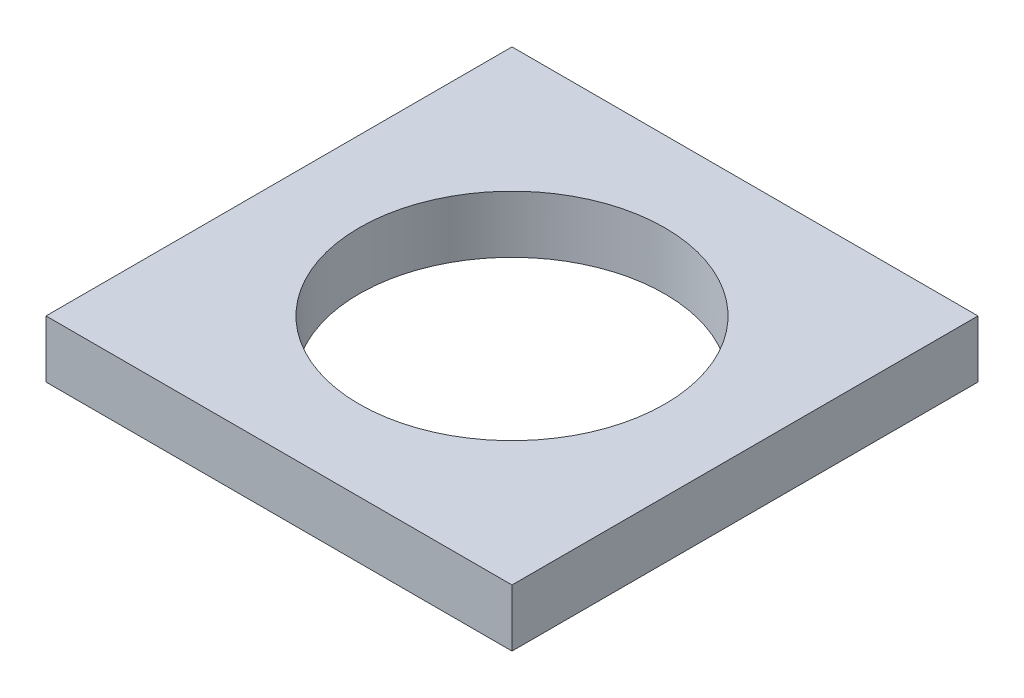
SolidWorks part; units mm, degrees
ref_plane "Front Plane" through (0, 0, 0) normal (0, 0, 1) x (1, 0, 0)
ref_plane "Top Plane" through (0, 0, 0) normal (0, 1, 0) x (1, 0, 0)
ref_plane "Right Plane" through (0, 0, 0) normal (1, 0, 0) x (0, 0, -1)
other "Configuration Table"
sketch "Sketch1" plane through (0, 0, 0) normal (0, 1, 0) x (1, 0, 0)
  line L0 (-6.1, -6.1) -> (6.1, -6.1)
  line L1 (6.1, -6.1) -> (6.1, 6.1)
  line L2 (6.1, 6.1) -> (-6.1, 6.1)
  line L3 (-6.1, 6.1) -> (-6.1, -6.1)
extrude "Seal" add sketch "Sketch1" along normal blind 1.5
sketch "Sketch2" plane through (0, 0, 0) normal (0, 1, 0) x (1, 0, 0)
  circle A0 centre (0, 0) radius 4
  dimension "D1" = 8
extrude "Water_Hole" cut sketch "Sketch2" along normal through all and the other way through all
equation "\"Jar_OD\"= 90  'ASSUMED - Part G fallback - jar outer diameter"
equation "\"Jar_H\"= 120  'ASSUMED - Part G fallback - jar height"
equation "\"Pump_L\"= 45  'ASSUMED - Part G fallback"
equation "\"Pump_W\"= 24  'ASSUMED - Part G fallback"
equation "\"Pump_H\"= 33  'ASSUMED - Part G fallback"
equation "\"Pump_Outlet_OD\"= 7.5  'ASSUMED - Part G fallback"
equation "\"Tube_OD\"= 8  'ASSUMED - Part G fallback"
equation "\"Tube_ID\"= 6  'ASSUMED - Part G fallback"
equation "\"TDS_Body_Dia\"= 12  'ASSUMED - Part G fallback"
equation "\"TDS_Wet_Len\"= 45  'ASSUMED - Part G fallback - length in water"
equation "\"DS_Tube_Dia\"= 6  'ASSUMED - Part G fallback"
equation "\"DS_Tube_Len\"= 50  'ASSUMED - Part G fallback"
equation "\"ORP_Body_Dia\"= 12  'ASSUMED - Part G fallback"
equation "\"ORP_Body_Len\"= 150  'ASSUMED - Part G fallback"
equation "\"ORP_Cap_Dia\"= 16  'ASSUMED - Part G fallback"
equation "\"Turb_W\"= 33  'ASSUMED - Part G fallback - head width"
equation "\"Turb_D\"= 28  'ASSUMED - Part G fallback - head depth"
equation "\"Turb_H\"= 30  'ASSUMED - Part G fallback - head height"
equation "\"Turb_Slot_W\"= 10  'ASSUMED - Part G fallback - slot width"
equation "\"Flow_L\"= 62  'ASSUMED - Part G fallback YF-S201"
equation "\"Flow_W\"= 36  'ASSUMED - Part G fallback"
equation "\"Flow_H\"= 35  'ASSUMED - Part G fallback"
equation "\"Thread_G12_OD\"= 20.955  'ASSUMED - Part G fallback thread G1/2 (major diameter)"
equation "\"Valve_L\"= 75  'ASSUMED - Part G fallback"
equation "\"Valve_W\"= 45  'ASSUMED - Part G fallback"
equation "\"Valve_H\"= 60  'ASSUMED - Part G fallback"
equation "\"Tee_L\"= 40  'ASSUMED - Part G fallback - overall length"
equation "\"Tee_Branch_L\"= 25  'ASSUMED - Part G fallback"
equation "\"Tee_OD\"= 12  'ASSUMED - Part G fallback"
equation "\"LED_Board_L\"= 20  'ASSUMED - Part G fallback"
equation "\"LED_Board_W\"= 20  'ASSUMED - Part G fallback - LED at centre"
equation "\"GUVA_L\"= 20  'ASSUMED - Part G fallback"
equation "\"GUVA_W\"= 12  'ASSUMED - Part G fallback - sensor at centre"
equation "\"Reed_L\"= 27  'ASSUMED - Part G fallback MC-38 half"
equation "\"Reed_W\"= 14  'ASSUMED - Part G fallback"
equation "\"Reed_H\"= 8  'ASSUMED - Part G fallback"
equation "\"ESP_L\"= 51  'ASSUMED - Part G fallback"
equation "\"ESP_W\"= 28  'ASSUMED - Part G fallback"
equation "\"TFT_L\"= 58  'ASSUMED - Part G fallback - board"
equation "\"TFT_W\"= 35  'ASSUMED - Part G fallback - board"
equation "\"TFT_Win_L\"= 35  'ASSUMED - Part G fallback - visible window"
equation "\"TFT_Win_W\"= 28  'ASSUMED - Part G fallback - visible window"
equation "\"Relay_L\"= 50  'ASSUMED - Part G fallback"
equation "\"Relay_W\"= 26  'ASSUMED - Part G fallback"
equation "\"Relay_H\"= 19  'ASSUMED - Part G fallback"
equation "\"Mosfet_L\"= 34  'ASSUMED - Part G fallback"
equation "\"Mosfet_W\"= 17  'ASSUMED - Part G fallback"
equation "\"Mosfet_H\"= 12  'ASSUMED - Part G fallback"
equation "\"TDS_Board_L\"= 42  'ASSUMED - Part G fallback"
equation "\"TDS_Board_W\"= 32  'ASSUMED - Part G fallback"
equation "\"Turb_Board_L\"= 38  'ASSUMED - Part G fallback"
equation "\"Turb_Board_W\"= 28  'ASSUMED - Part G fallback"
equation "\"BNC_Thread_Dia\"= 9.5  'ASSUMED - Part G fallback"
equation "\"Plate_L\"= 420  'ASSUMED - Part G fallback"
equation "\"Plate_W\"= 297  'ASSUMED - Part G fallback"
equation "\"Plate_T\"= 6  'ASSUMED - Part G fallback"
equation "\"Booster_L\"= 150  'ASSUMED - Part G fallback - booster pump"
equation "\"Booster_W\"= 95  'ASSUMED - Part G fallback"
equation "\"Booster_H\"= 100  'ASSUMED - Part G fallback"
equation "\"PTube_OD\"= 6.35  'ASSUMED - Part G fallback - product tube 1/4 inch"
equation "\"Qz_Out\"= 12  'ASSUMED - Part G fallback - quartz channel outside square"
equation "\"Qz_Path\"= 10  'ASSUMED - Part G fallback - quartz channel inside light path"
equation "\"Qz_L\"= 40  'ASSUMED - Part G fallback - quartz channel length"
equation "\"LED860_Dia\"= 5  'ASSUMED - Part G fallback - 860 nm LED"
equation "\"BPW_L\"= 5.4  'ASSUMED - Part G fallback - BPW34"
equation "\"BPW_W\"= 4.3  'ASSUMED - Part G fallback - BPW34"
equation "\"Cart_Dia\"= 50  'ASSUMED - Part G fallback - sediment and pre-carbon cartridges"
equation "\"Cart_L\"= 255  'ASSUMED - Part G fallback"
equation "\"UF_Dia\"= 50  'ASSUMED - Part G fallback - UF cartridge"
equation "\"UF_L\"= 260  'ASSUMED - Part G fallback"
equation "\"RO_Dia\"= 62  'ASSUMED - Part G fallback - RO membrane housing"
equation "\"RO_L\"= 300  'ASSUMED - Part G fallback"
equation "\"UVC_Dia\"= 40  'ASSUMED - Part G fallback - UV-C chamber"
equation "\"UVC_L\"= 300  'ASSUMED - Part G fallback"
equation "\"Tank_W\"= 260  'ASSUMED - Part G fallback - storage tank"
equation "\"Tank_D\"= 160  'ASSUMED - Part G fallback"
equation "\"Tank_H\"= 300  'ASSUMED - Part G fallback"
equation "\"Cab_W\"= 400  'ASSUMED - Part G fallback - purifier cabinet"
equation "\"Cab_D\"= 270  'ASSUMED - Part G fallback"
equation "\"Cab_H\"= 560  'ASSUMED - Part G fallback"
equation "\"ORP_Board_L\"= 40  'ASSUMED - Part G fallback - ORP buffer board"
equation "\"ORP_Board_W\"= 30  'ASSUMED - Part G fallback"
equation "\"Opt_Board_L\"= 50  'ASSUMED - Part G fallback - optical front-end board"
equation "\"Opt_Board_W\"= 40  'ASSUMED - Part G fallback"
equation "\"Buck_L\"= 43  'ASSUMED - Part G fallback - 12 V to 5 V buck module"
equation "\"Buck_W\"= 21  'ASSUMED - Part G fallback"
equation "\"Buck_H\"= 14  'ASSUMED - Part G fallback"
equation "\"BB_L\"= 165  'ASSUMED - Part G fallback - breadboard (As_Built_R3 only)"
equation "\"BB_W\"= 55  'ASSUMED - Part G fallback"
equation "\"BB_H\"= 10  'ASSUMED - Part G fallback"
equation "\"Cuv_W\"= 12.5  'ASSUMED - old R3 cuvette (station suppressed in SS4)"
equation "\"Cuv_D\"= 12.5  'ASSUMED - old R3 cuvette (station suppressed in SS4)"
equation "\"Cuv_H\"= 45  'ASSUMED - old R3 cuvette (station suppressed in SS4)"
equation "\"Probe_Clr\"= 0.3  'DESIGN VALUE - Part C rule 3 - printed probe hole = diameter + 0.3"
equation "\"Label_H\"= 0.6  'DESIGN VALUE - Part D - raised label height"
